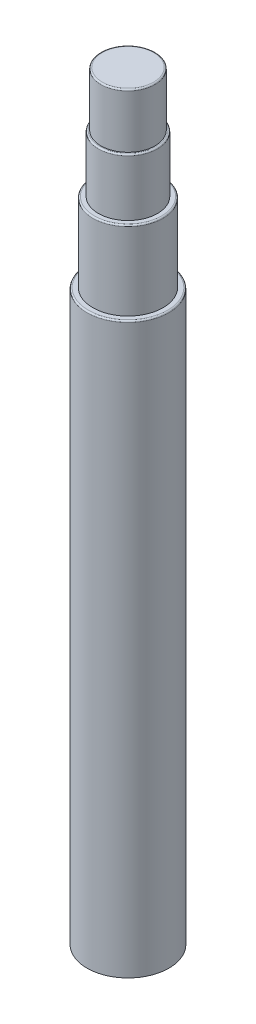
SolidWorks part; units mm, degrees
ref_plane "Front Plane" through (0, 0, 0) normal (0, 0, 1) x (1, 0, 0)
ref_plane "Top Plane" through (0, 0, 0) normal (0, 1, 0) x (1, 0, 0)
ref_plane "Right Plane" through (0, 0, 0) normal (1, 0, 0) x (0, 0, -1)
sketch "Sketch1" plane through (0, 0, 0) normal (0, 1, 0) x (1, 0, 0)
  circle A0 centre (0, 0) radius 28.575
  dimension "D1" = 57.15
extrude "Boss-Extrude1" add sketch "Sketch1" along normal blind 397
sketch "Sketch2" plane through (0, 397, 0) normal (0, 1, 0) x (1, 0, 0)
  circle A0 centre (0, 0) radius 24.5
  dimension "D1" = 49
extrude "Boss-Extrude2" add sketch "Sketch2" along normal blind 55
sketch "Sketch3" plane through (0, 452, 0) normal (0, 1, 0) x (1, 0, 0)
  circle A0 centre (0, 0) radius 20.64
  dimension "D1" = 41.28
extrude "Boss-Extrude3" add sketch "Sketch3" along normal blind 40
sketch "Sketch4" plane through (0, 492, 0) normal (0, 1, 0) x (1, 0, 0)
  circle A0 centre (0, 0) radius 18.9
  dimension "D1" = 37.8
extrude "Boss-Extrude4" add sketch "Sketch4" along normal blind 38
fillet "Fillet1" radius 1 4 edges at (0, 397, 28.575) (0, 452, 24.5) (0, 492, 20.64) (0, 530, 18.9)
sketch "Sketch5" plane through (0, 0, 0) normal (0, -1, 0) x (1, 0, 0)
  circle A0 centre (0, 0) radius 5
  dimension "D1" = 10
extrude "Boss-Extrude5" add sketch "Sketch5" along normal blind 5
